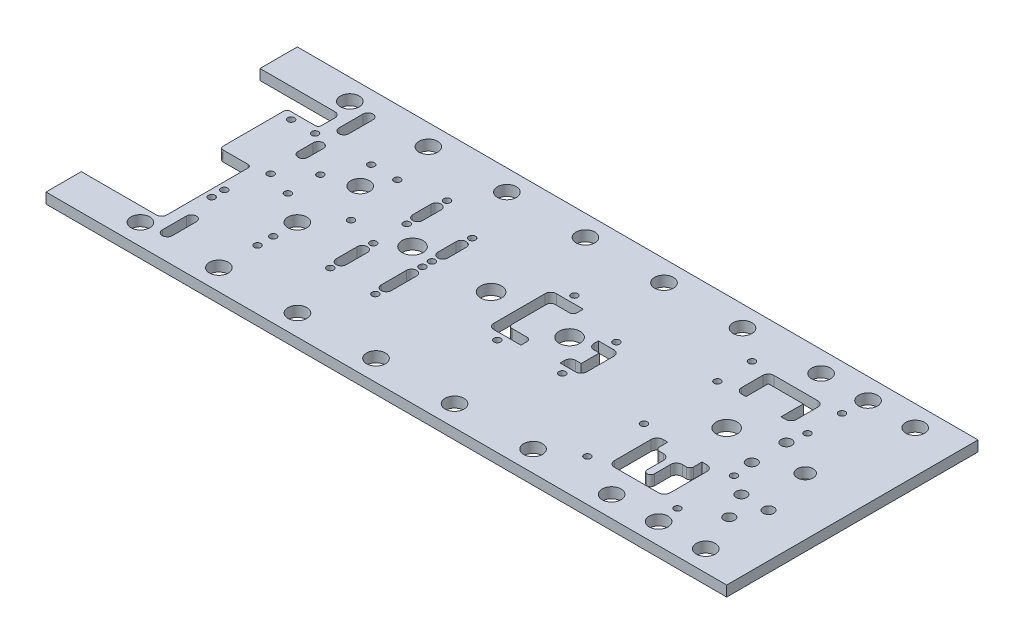
SolidWorks part; units mm, degrees
material "K110"
ref_plane "Front Plane" through (0, 0, 0) normal (0, 0, 1) x (1, 0, 0)
ref_plane "Top Plane" through (0, 0, 0) normal (0, 1, 0) x (1, 0, 0)
ref_plane "Right Plane" through (0, 0, 0) normal (1, 0, 0) x (0, 0, -1)
sketch "Sketch1" plane through (0, 0, 0) normal (0, 1, 0) x (1, 0, 0)
  line L1 (-325, -120) -> (325, -120)
  line L2 (-325, -120) -> (-325, 120)
  line L3 (-325, 120) -> (325, 120)
  line L4 (325, -120) -> (325, 120)
  line L5 (-325, -120) -> (325, 120) construction
  line L6 (-325, 120) -> (325, -120) construction
  point P0 (0, 0)
  dimension "D1" = 650
  dimension "D2" = 240
extrude "Boss-Extrude1" add sketch "Sketch1" against normal blind 10
sketch "Sketch2" plane through (0, -10, 0) normal (0, -1, 0) x (1, 0, 0)
  circle A0 centre (-254.87, 100) radius 9 construction
  circle A1 centre (-254.87, -100) radius 9
  circle A2 centre (-254.87, -100) radius 9
  circle A3 centre (285, -100) radius 9
  circle A4 centre (285, -100) radius 9
  circle A5 centre (120.13, 100) radius 9
  circle A6 centre (120.13, 100) radius 9
  circle A7 centre (120.13, -100) radius 9
  circle A8 centre (120.13, -100) radius 9
  circle A9 centre (45.13, 100) radius 9
  circle A10 centre (45.13, 100) radius 9
  circle A11 centre (240, 100) radius 9
  circle A12 centre (240, 100) radius 9
  circle A13 centre (240, -100) radius 9
  circle A14 centre (240, -100) radius 9
  circle A15 centre (195.13, -100) radius 9
  circle A16 centre (195.13, -100) radius 9
  circle A17 centre (285, 100) radius 9
  circle A18 centre (285, 100) radius 9
  circle A19 centre (-104.87, -100) radius 9
  circle A20 centre (-104.87, -100) radius 9
  circle A21 centre (-179.87, 100) radius 9
  circle A22 centre (-179.87, 100) radius 9
  circle A23 centre (-179.87, -100) radius 9
  circle A24 centre (-179.87, -100) radius 9
  circle A25 centre (45.13, -100) radius 9
  circle A26 centre (45.13, -100) radius 9
  circle A27 centre (-29.87, 100) radius 9
  circle A28 centre (-29.87, 100) radius 9
  circle A29 centre (-29.87, -100) radius 9
  circle A30 centre (-29.87, -100) radius 9
  circle A31 centre (-104.87, 100) radius 9
  circle A32 centre (-104.87, 100) radius 9
  circle A33 centre (195.13, 100) radius 9
  circle A34 centre (195.13, 100) radius 9
  circle A35 centre (-254.87, 100) radius 9
  circle A36 centre (195.13, -9.86) radius 10 construction
  circle A37 centre (45.13, -9.86) radius 10 construction
  circle A38 centre (-29.87, -9.86) radius 10 construction
  circle A39 centre (-104.87, -9.86) radius 10 construction
  circle A40 centre (-179.87, 25.14) radius 9 construction
  circle A41 centre (-179.87, -34.86) radius 9 construction
  circle A42 centre (195.13, -9.86) radius 10
  circle A43 centre (45.13, -9.86) radius 10
  circle A44 centre (-29.87, -9.86) radius 10
  circle A45 centre (-104.87, -9.86) radius 10
  circle A46 centre (-179.87, 25.14) radius 9
  circle A47 centre (-179.87, -34.86) radius 9
  dimension "D1" = 0
  dimension "D2" = 0
  dimension "D3" = 0
  dimension "D4" = 0
  dimension "D5" = 0
  dimension "D6" = 0
  dimension "D7" = 0
  dimension "D8" = 0
  dimension "D9" = 0
  dimension "D10" = 0
  dimension "D11" = 0
  dimension "D12" = 0
  dimension "D13" = 0
  dimension "D14" = 0
  dimension "D15" = 0
  dimension "D16" = 0
  dimension "D17" = 0
extrude "Cut-Extrude1" cut sketch "Sketch2" against normal up to next
hole_wizard "M6 Clearance Hole1" positions "Sketch7" profile "Sketch6" hole size "M6" standard "ISO" end condition through all
sketch "Sketch7" plane through (0, -10, 0) normal (0, -1, 0) x (-1, 0, 0)
  line L0 (232.87, -8.64) -> (232.87, 13.36) construction
  point P0 (-238.13, -26.14)
  point P3 (-152.13, -26.14)
  point P6 (-152.13, -80.14)
  point P9 (-238.13, -80.14)
  point P12 (-238.13, 77)
  point P15 (-152.13, 77)
  point P18 (-152.13, 44)
  point P21 (-238.13, 44)
  point P24 (-71.5, -23.4862)
  point P27 (-71.5, 28.2062)
  point P30 (-12.94, -26.9862)
  point P33 (-12.94, 46.7062)
  point P36 (83.37, 45.36)
  point P39 (83.37, 6.86)
  point P42 (126.37, 25.86)
  point P45 (126.37, 64.36)
  point P48 (83.37, -2.14)
  point P51 (126.37, -6.14)
  point P54 (126.37, -47.14)
  point P57 (83.37, -47.14)
  point P60 (156.12, 2.36)
  point P63 (208.37, -5.64)
  point P66 (208.37, 25.36)
  point P69 (192.37, 57.86)
  point P72 (167.37, 57.86)
  point P75 (179.87, -48.14)
  point P78 (179.87, -63.14)
  point P81 (241.62, -33.14)
  point P84 (241.62, -45.14)
  point P87 (232.87, 2.36)
  point P91 (267.87, 56.92)
  point P94 (245.0007, 56.92)
sketch "Sketch6" plane through (238.13, -10, 26.14) normal (1, 0, 0) x (0, 0, -1)
  line L0 (0, 0) -> (0, 10)
  line L1 (0, 10) -> (3.2, 10)
  line L2 (3.2, 10) -> (3.2, 0.025)
  line L3 (3.2, 0.025) -> (3.225, 0)
  line L5 (3.225, 0) -> (0, 0)
  line L6 (-3.2, 0.025) -> (-3.225, 0) construction
  line L11 (0, -6.35) -> (0, 107.95) construction
  dimension "Thru Hole Dia." = 6.4
  dimension "Thru Hole Depth" = 10
  dimension "Near C'Sink Dia." = 6.45
  dimension "Near C'Sink Angle" = 90
sketch "Sketch8" plane through (0, 0, 0) normal (0, 1, 0) x (1, 0, 0)
  line L0 (-325, -86.2624) -> (-253.37, -86.2624) construction
  line L2 (-248.37, -52.14) -> (-248.37, -14.64) construction
  line L3 (-278.37, 33.36) -> (-278.37, -0.64) construction
  line L4 (-248.37, 63.475) -> (-248.37, 79.36) construction
  line L5 (-253.37, 84.36) -> (-325, 84.36) construction
  line L6 (-325, -86.2624) -> (-253.37, -86.2624)
  line L8 (-248.37, -81.2624) -> (-248.37, -3.64)
  line L9 (-278.37, 63.48) -> (-278.37, -0.64)
  line L10 (-248.37, 63.48) -> (-248.37, 79.36)
  line L11 (-253.37, 84.36) -> (-325, 84.36)
  line L12 (-273.87, 63.48) -> (-237.87, 63.48) construction
  line L13 (-278.37, 63.48) -> (-248.37, 63.48)
  line L14 (-325, 84.36) -> (-325, -86.2624)
  line L15 (-251.37, -0.64) -> (-270.37, -0.64) construction
  line L16 (-251.37, -0.64) -> (-278.37, -0.64)
  arc A0 (-253.37, -86.2624) -> (-248.37, -81.2624) centre (-253.37, -81.2624) ccw construction
  arc A1 (-248.37, 79.36) -> (-253.37, 84.36) centre (-253.37, 79.36) ccw construction
  arc A2 (-253.37, -86.2624) -> (-248.37, -81.2624) centre (-253.37, -81.2624) ccw
  arc A3 (-248.37, 79.36) -> (-253.37, 84.36) centre (-253.37, 79.36) ccw
  arc A4 (-248.37, -3.64) -> (-251.37, -0.64) centre (-251.37, -3.64) ccw construction
  arc A5 (-248.37, -3.64) -> (-251.37, -0.64) centre (-251.37, -3.64) ccw
extrude "Cut-Extrude2" cut sketch "Sketch8" against normal up to next
fillet "Fillet1" radius 3 3 edges at (-248.37, -5, -63.48) (-278.37, -5, -63.48) (-278.37, -5, 0.64)
sketch "Sketch12" plane through (0, -10, 0) normal (0, -1, 0) x (1, 0, 0)
  line L18 (211.8377, -45.0677) -> (211.8377, -66.3477)
  line L19 (178.4223, -66.3477) -> (178.4223, -45.0677)
  line L20 (211.8377, -66.3477) -> (178.4223, -66.3477)
  line L21 (216.13, -45.0677) -> (211.8377, -45.0677)
  line L22 (221.4223, -70.64) -> (221.4223, -50.36)
  line L23 (195.13, -75.9323) -> (216.13, -75.9323)
  line L24 (174.13, -75.9323) -> (195.13, -75.9323)
  line L25 (178.4223, -45.0677) -> (174.13, -45.0677)
  line L26 (168.8377, -50.36) -> (168.8377, -70.64)
  line L27 (211.8377, -45.0677) -> (211.8377, -66.3477)
  line L28 (178.4223, -66.3477) -> (178.4223, -45.0677)
  line L29 (211.8377, -66.3477) -> (178.4223, -66.3477)
  line L30 (216.13, -45.0677) -> (211.8377, -45.0677)
  line L31 (221.4223, -70.64) -> (221.4223, -50.36)
  line L32 (195.13, -75.9323) -> (216.13, -75.9323)
  line L33 (174.13, -75.9323) -> (195.13, -75.9323)
  line L34 (178.4223, -45.0677) -> (174.13, -45.0677)
  line L35 (168.8377, -50.36) -> (168.8377, -70.64)
  line L51 (211.5164, 30.0264) -> (216.13, 30.0264)
  line L52 (221.7436, 35.64) -> (221.7436, 53.14)
  line L53 (221.7436, 53.14) -> (221.7436, 70.64)
  line L54 (216.13, 76.2536) -> (174.13, 76.2536)
  line L55 (168.5164, 70.64) -> (168.5164, 35.64)
  line L56 (174.13, 30.0264) -> (178.7436, 30.0264)
  line L57 (211.5164, 38.14) -> (211.5164, 30.0264)
  line L58 (204.13, 41.5264) -> (208.13, 41.5264)
  line L59 (198.5164, 62.64) -> (198.5164, 47.14)
  line L60 (191.7436, 47.14) -> (191.7436, 62.64)
  line L61 (182.13, 41.5264) -> (186.13, 41.5264)
  line L62 (178.7436, 30.0264) -> (178.7436, 38.14)
  line L63 (211.5164, 30.0264) -> (216.13, 30.0264)
  line L64 (221.7436, 35.64) -> (221.7436, 53.14)
  line L65 (221.7436, 53.14) -> (221.7436, 70.64)
  line L66 (216.13, 76.2536) -> (174.13, 76.2536)
  line L67 (168.5164, 70.64) -> (168.5164, 35.64)
  line L68 (174.13, 30.0264) -> (178.7436, 30.0264)
  line L69 (211.5164, 38.14) -> (211.5164, 30.0264)
  line L70 (204.13, 41.5264) -> (208.13, 41.5264)
  line L71 (198.5164, 62.64) -> (198.5164, 47.14)
  line L72 (191.7436, 47.14) -> (191.7436, 62.64)
  line L73 (182.13, 41.5264) -> (186.13, 41.5264)
  line L74 (178.7436, 30.0264) -> (178.7436, 38.14)
  arc A8 (221.4223, -50.36) -> (216.13, -45.0677) centre (216.13, -50.36) ccw
  arc A9 (216.13, -75.9323) -> (221.4223, -70.64) centre (216.13, -70.64) ccw
  arc A10 (174.13, -45.0677) -> (168.8377, -50.36) centre (174.13, -50.36) ccw
  arc A11 (168.8377, -70.64) -> (174.13, -75.9323) centre (174.13, -70.64) ccw
  arc A12 (221.4223, -50.36) -> (216.13, -45.0677) centre (216.13, -50.36) ccw
  arc A13 (216.13, -75.9323) -> (221.4223, -70.64) centre (216.13, -70.64) ccw
  arc A14 (174.13, -45.0677) -> (168.8377, -50.36) centre (174.13, -50.36) ccw
  arc A15 (168.8377, -70.64) -> (174.13, -75.9323) centre (174.13, -70.64) ccw
  arc A30 (216.13, 30.0264) -> (221.7436, 35.64) centre (216.13, 35.64) ccw
  arc A31 (221.7436, 70.64) -> (216.13, 76.2536) centre (216.13, 70.64) ccw
  arc A32 (174.13, 76.2536) -> (168.5164, 70.64) centre (174.13, 70.64) ccw
  arc A33 (168.5164, 35.64) -> (174.13, 30.0264) centre (174.13, 35.64) ccw
  arc A34 (211.5164, 38.14) -> (208.13, 41.5264) centre (208.13, 38.14) ccw
  arc A35 (198.5164, 47.14) -> (204.13, 41.5264) centre (204.13, 47.14) ccw
  arc A36 (198.5164, 62.64) -> (191.7436, 62.64) centre (195.13, 62.64) ccw
  arc A37 (186.13, 41.5264) -> (191.7436, 47.14) centre (186.13, 47.14) ccw
  arc A38 (182.13, 41.5264) -> (178.7436, 38.14) centre (182.13, 38.14) ccw
  arc A39 (216.13, 30.0264) -> (221.7436, 35.64) centre (216.13, 35.64) ccw
  arc A40 (221.7436, 70.64) -> (216.13, 76.2536) centre (216.13, 70.64) ccw
  arc A41 (174.13, 76.2536) -> (168.5164, 70.64) centre (174.13, 70.64) ccw
  arc A42 (168.5164, 35.64) -> (174.13, 30.0264) centre (174.13, 35.64) ccw
  arc A43 (211.5164, 38.14) -> (208.13, 41.5264) centre (208.13, 38.14) ccw
  arc A44 (198.5164, 47.14) -> (204.13, 41.5264) centre (204.13, 47.14) ccw
  arc A45 (198.5164, 62.64) -> (191.7436, 62.64) centre (195.13, 62.64) ccw
  arc A46 (186.13, 41.5264) -> (191.7436, 47.14) centre (186.13, 47.14) ccw
  arc A47 (182.13, 41.5264) -> (178.7436, 38.14) centre (182.13, 38.14) ccw
  circle A1945 centre (270.13, 62.64) radius 5.1136
  circle A1946 centre (270.13, 62.64) radius 5.1136
  circle A1948 centre (283.13, 38.14) radius 5.1136
  circle A1949 centre (283.13, 38.14) radius 5.1136
  circle A1951 centre (257.13, 38.14) radius 5.1136
  circle A1952 centre (257.13, 38.14) radius 5.1136
  circle A1954 centre (270.13, -9.86) radius 7.6136
  circle A1955 centre (270.13, -9.86) radius 7.6136
  circle A1957 centre (235.63, -26.36) radius 5.1136
  circle A1958 centre (235.63, -26.36) radius 5.1136
  circle A1960 centre (235.63, 6.64) radius 5.1136
  circle A1961 centre (235.63, 6.64) radius 5.1136
  dimension "D1" = 1.6
  dimension "D2" = 1.6
  dimension "D3" = 1.6
  dimension "D4" = 1.6
  dimension "D5" = 1.6
  dimension "D6" = 1.6
  dimension "D7" = 1.6
  dimension "D8" = 1.6
extrude "Cut-Extrude3" cut sketch "Sketch12" against normal up to next
sketch "Sketch13" plane through (0, -10, 0) normal (0, -1, 0) x (1, 0, 0)
  line L72 (61.8377, 15.9323) -> (61.8377, 11.64)
  line L73 (67.13, 6.3477) -> (72.3377, 6.3477)
  line L74 (72.3377, 6.3477) -> (72.3377, -11.0677)
  line L75 (72.3377, -11.0677) -> (67.13, -11.0677)
  line L76 (61.8377, -16.36) -> (61.8377, -20.6523)
  line L77 (76.63, 15.9323) -> (61.8377, 15.9323)
  line L78 (81.9223, -2.36) -> (81.9223, 10.64)
  line L79 (81.9223, -15.36) -> (81.9223, -2.36)
  line L80 (61.8377, -20.6523) -> (76.63, -20.6523)
  line L81 (61.8377, 15.9323) -> (61.8377, 11.64)
  line L82 (67.13, 6.3477) -> (72.3377, 6.3477)
  line L83 (72.3377, 6.3477) -> (72.3377, -11.0677)
  line L84 (72.3377, -11.0677) -> (67.13, -11.0677)
  line L85 (61.8377, -16.36) -> (61.8377, -20.6523)
  line L86 (76.63, 15.9323) -> (61.8377, 15.9323)
  line L87 (81.9223, -2.36) -> (81.9223, 10.64)
  line L88 (81.9223, -15.36) -> (81.9223, -2.36)
  line L89 (61.8377, -20.6523) -> (76.63, -20.6523)
  line L99 (2.63, -39.6523) -> (28.4223, -39.6523)
  line L100 (-2.6623, -13.23) -> (-2.6623, -34.36)
  line L101 (-2.6623, 14.64) -> (-2.6623, -13.23)
  line L102 (28.4223, 19.9323) -> (2.63, 19.9323)
  line L103 (28.4223, 14.14) -> (28.4223, 19.9323)
  line L104 (28.4223, -39.6523) -> (28.4223, -33.86)
  line L105 (24.63, -30.0677) -> (10.63, -30.0677)
  line L106 (6.9223, -26.36) -> (6.9223, 6.64)
  line L107 (10.63, 10.3477) -> (24.63, 10.3477)
  line L108 (2.63, -39.6523) -> (28.4223, -39.6523)
  line L109 (-2.6623, -13.23) -> (-2.6623, -34.36)
  line L110 (-2.6623, 14.64) -> (-2.6623, -13.23)
  line L111 (28.4223, 19.9323) -> (2.63, 19.9323)
  line L112 (28.4223, 14.14) -> (28.4223, 19.9323)
  line L113 (28.4223, -39.6523) -> (28.4223, -33.86)
  line L114 (24.63, -30.0677) -> (10.63, -30.0677)
  line L115 (6.9223, -26.36) -> (6.9223, 6.64)
  line L116 (10.63, 10.3477) -> (24.63, 10.3477)
  arc A48 (61.8377, 11.64) -> (67.13, 6.3477) centre (67.13, 11.64) ccw
  arc A49 (67.13, -11.0677) -> (61.8377, -16.36) centre (67.13, -16.36) ccw
  arc A50 (81.9223, 10.64) -> (76.63, 15.9323) centre (76.63, 10.64) ccw
  arc A51 (76.63, -20.6523) -> (81.9223, -15.36) centre (76.63, -15.36) ccw
  arc A52 (61.8377, 11.64) -> (67.13, 6.3477) centre (67.13, 11.64) ccw
  arc A53 (67.13, -11.0677) -> (61.8377, -16.36) centre (67.13, -16.36) ccw
  arc A54 (81.9223, 10.64) -> (76.63, 15.9323) centre (76.63, 10.64) ccw
  arc A55 (76.63, -20.6523) -> (81.9223, -15.36) centre (76.63, -15.36) ccw
  arc A62 (-2.6623, -34.36) -> (2.63, -39.6523) centre (2.63, -34.36) ccw
  arc A63 (2.63, 19.9323) -> (-2.6623, 14.64) centre (2.63, 14.64) ccw
  arc A64 (28.4223, -33.86) -> (24.63, -30.0677) centre (24.63, -33.86) ccw
  arc A65 (6.9223, -26.36) -> (10.63, -30.0677) centre (10.63, -26.36) ccw
  arc A66 (10.63, 10.3477) -> (6.9223, 6.64) centre (10.63, 6.64) ccw
  arc A67 (24.63, 10.3477) -> (28.4223, 14.14) centre (24.63, 14.14) ccw
  arc A68 (-2.6623, -34.36) -> (2.63, -39.6523) centre (2.63, -34.36) ccw
  arc A69 (2.63, 19.9323) -> (-2.6623, 14.64) centre (2.63, 14.64) ccw
  arc A70 (28.4223, -33.86) -> (24.63, -30.0677) centre (24.63, -33.86) ccw
  arc A71 (6.9223, -26.36) -> (10.63, -30.0677) centre (10.63, -26.36) ccw
  arc A72 (10.63, 10.3477) -> (6.9223, 6.64) centre (10.63, 6.64) ccw
  arc A73 (24.63, 10.3477) -> (28.4223, 14.14) centre (24.63, 14.14) ccw
  dimension "D1" = 1.6
  dimension "D2" = 1.6
extrude "Cut-Extrude4" cut sketch "Sketch13" against normal up to next
sketch "Sketch14" plane through (0, -10, 0) normal (0, -1, 0) x (1, 0, 0)
  line L8 (-88.1623, -17.31) -> (-88.1623, -34.91)
  line L9 (-78.5777, -26.11) -> (-78.5777, -17.31)
  line L10 (-78.5777, -34.91) -> (-78.5777, -26.11)
  line L11 (-88.1623, -17.31) -> (-88.1623, -34.91)
  line L12 (-78.5777, -26.11) -> (-78.5777, -17.31)
  line L13 (-78.5777, -34.91) -> (-78.5777, -26.11)
  line L17 (-78.5777, 12.59) -> (-78.5777, 24.64)
  line L18 (-88.1623, 36.69) -> (-88.1623, 12.59)
  line L19 (-78.5777, 24.64) -> (-78.5777, 36.69)
  line L20 (-78.5777, 12.59) -> (-78.5777, 24.64)
  line L21 (-88.1623, 36.69) -> (-88.1623, 12.59)
  line L22 (-78.5777, 24.64) -> (-78.5777, 36.69)
  line L26 (-131.2322, 36.69) -> (-131.2322, 16.59)
  line L27 (-121.5078, 26.64) -> (-121.5078, 36.69)
  line L28 (-121.5078, 16.59) -> (-121.5078, 26.64)
  line L29 (-131.2322, 36.69) -> (-131.2322, 16.59)
  line L30 (-121.5078, 26.64) -> (-121.5078, 36.69)
  line L31 (-121.5078, 16.59) -> (-121.5078, 26.64)
  line L35 (-131.1623, -36.31) -> (-131.1623, -53.91)
  line L36 (-121.5777, -45.11) -> (-121.5777, -36.31)
  line L37 (-121.5777, -53.91) -> (-121.5777, -45.11)
  line L38 (-131.1623, -36.31) -> (-131.1623, -53.91)
  line L39 (-121.5777, -45.11) -> (-121.5777, -36.31)
  line L40 (-121.5777, -53.91) -> (-121.5777, -45.11)
  arc A6 (-88.1623, -34.91) -> (-78.5777, -34.91) centre (-83.37, -34.91) ccw
  arc A7 (-78.5777, -17.31) -> (-88.1623, -17.31) centre (-83.37, -17.31) ccw
  arc A8 (-88.1623, -34.91) -> (-78.5777, -34.91) centre (-83.37, -34.91) ccw
  arc A9 (-78.5777, -17.31) -> (-88.1623, -17.31) centre (-83.37, -17.31) ccw
  arc A12 (-88.1623, 12.59) -> (-78.5777, 12.59) centre (-83.37, 12.59) ccw
  arc A13 (-78.5777, 36.69) -> (-88.1623, 36.69) centre (-83.37, 36.69) ccw
  arc A14 (-88.1623, 12.59) -> (-78.5777, 12.59) centre (-83.37, 12.59) ccw
  arc A15 (-78.5777, 36.69) -> (-88.1623, 36.69) centre (-83.37, 36.69) ccw
  arc A18 (-131.2322, 16.59) -> (-121.5078, 16.59) centre (-126.37, 16.59) ccw
  arc A19 (-121.5078, 36.69) -> (-131.2322, 36.69) centre (-126.37, 36.69) ccw
  arc A20 (-131.2322, 16.59) -> (-121.5078, 16.59) centre (-126.37, 16.59) ccw
  arc A21 (-121.5078, 36.69) -> (-131.2322, 36.69) centre (-126.37, 36.69) ccw
  arc A24 (-131.1623, -53.91) -> (-121.5777, -53.91) centre (-126.37, -53.91) ccw
  arc A25 (-121.5777, -36.31) -> (-131.1623, -36.31) centre (-126.37, -36.31) ccw
  arc A26 (-131.1623, -53.91) -> (-121.5777, -53.91) centre (-126.37, -53.91) ccw
  arc A27 (-121.5777, -36.31) -> (-131.1623, -36.31) centre (-126.37, -36.31) ccw
  dimension "D1" = 1.6
  dimension "D2" = 1.6
  dimension "D3" = 1.6
  dimension "D4" = 1.6
extrude "Cut-Extrude5" cut sketch "Sketch14" against normal up to next
sketch "Sketch15" plane through (0, -10, 0) normal (0, -1, 0) x (1, 0, 0)
  line L6 (-228.5777, -95.77) -> (-228.5777, -84.32)
  line L7 (-228.5777, -84.32) -> (-228.5777, -72.87)
  line L8 (-238.1623, -72.87) -> (-238.1623, -95.77)
  line L9 (-228.5777, -95.77) -> (-228.5777, -84.32)
  line L10 (-228.5777, -84.32) -> (-228.5777, -72.87)
  line L11 (-238.1623, -72.87) -> (-238.1623, -95.77)
  line L15 (-238.1623, -33.86) -> (-238.1623, -48.36)
  line L16 (-228.5777, -41.11) -> (-228.5777, -33.86)
  line L17 (-228.5777, -48.36) -> (-228.5777, -41.11)
  line L18 (-238.1623, -33.86) -> (-238.1623, -48.36)
  line L19 (-228.5777, -41.11) -> (-228.5777, -33.86)
  line L20 (-228.5777, -48.36) -> (-228.5777, -41.11)
  line L24 (-238.1623, 95.77) -> (-238.1623, 72.87)
  line L25 (-228.5777, 84.32) -> (-228.5777, 95.77)
  line L26 (-228.5777, 72.87) -> (-228.5777, 84.32)
  line L27 (-238.1623, 95.77) -> (-238.1623, 72.87)
  line L28 (-228.5777, 84.32) -> (-228.5777, 95.77)
  line L29 (-228.5777, 72.87) -> (-228.5777, 84.32)
  arc A4 (-228.5777, -72.87) -> (-238.1623, -72.87) centre (-233.37, -72.87) ccw
  arc A5 (-238.1623, -95.77) -> (-228.5777, -95.77) centre (-233.37, -95.77) ccw
  arc A6 (-228.5777, -72.87) -> (-238.1623, -72.87) centre (-233.37, -72.87) ccw
  arc A7 (-238.1623, -95.77) -> (-228.5777, -95.77) centre (-233.37, -95.77) ccw
  arc A10 (-228.5777, -33.86) -> (-238.1623, -33.86) centre (-233.37, -33.86) ccw
  arc A11 (-238.1623, -48.36) -> (-228.5777, -48.36) centre (-233.37, -48.36) ccw
  arc A12 (-228.5777, -33.86) -> (-238.1623, -33.86) centre (-233.37, -33.86) ccw
  arc A13 (-238.1623, -48.36) -> (-228.5777, -48.36) centre (-233.37, -48.36) ccw
  arc A16 (-228.5777, 95.77) -> (-238.1623, 95.77) centre (-233.37, 95.77) ccw
  arc A17 (-238.1623, 72.87) -> (-228.5777, 72.87) centre (-233.37, 72.87) ccw
  arc A18 (-228.5777, 95.77) -> (-238.1623, 95.77) centre (-233.37, 95.77) ccw
  arc A19 (-238.1623, 72.87) -> (-228.5777, 72.87) centre (-233.37, 72.87) ccw
  dimension "D1" = 1.6
  dimension "D2" = 1.6
  dimension "D3" = 1.6
extrude "Cut-Extrude6" cut sketch "Sketch15" against normal up to next
